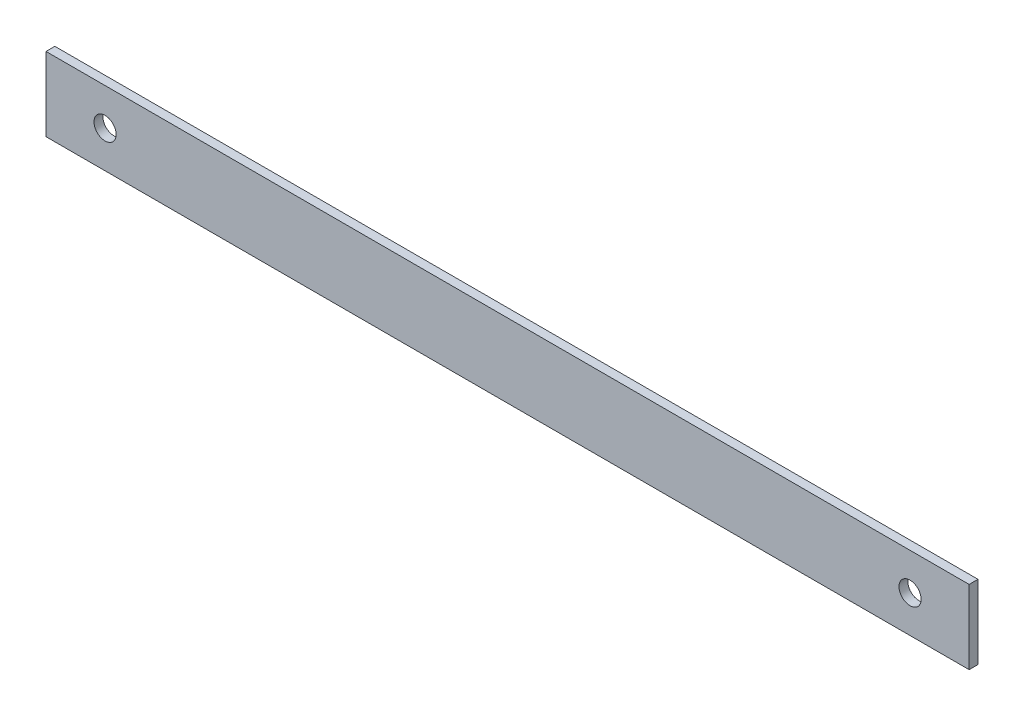
SolidWorks part; units mm, degrees
material "Brass"
ref_plane "Front Plane" through (0, 0, 0) normal (0, 0, 1) x (1, 0, 0)
ref_plane "Top Plane" through (0, 0, 0) normal (0, 1, 0) x (1, 0, 0)
ref_plane "Right Plane" through (0, 0, 0) normal (1, 0, 0) x (0, 0, -1)
sketch "Sketch1" plane through (0, 0, 0) normal (0, 0, 1) x (1, 0, 0)
  line L0 (0, 0) -> (125, 0)
  line L1 (125, 0) -> (125, 10)
  line L2 (125, 10) -> (0, 10)
  line L3 (0, 10) -> (0, 0)
extrude "Boss-Extrude1" add sketch "Sketch1" along normal blind 1.2
sketch "Sketch2" plane through (0, 0, 0) normal (0, 0, 1) x (1, 0, 0)
  circle A0 centre (8, 5) radius 1.5
  circle A1 centre (117, 5) radius 1.5
  dimension "D1" = 3
  dimension "D2" = 3
extrude "Cut-Extrude1" cut sketch "Sketch2" against normal mid plane 10
